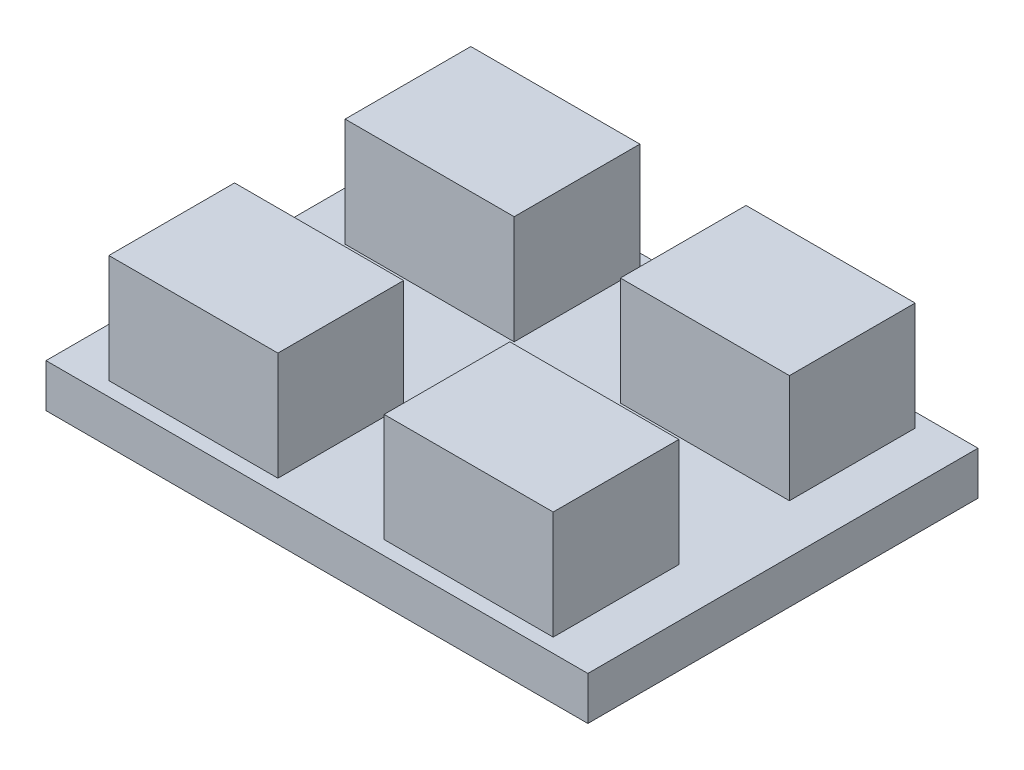
SolidWorks part; units mm, degrees
ref_plane "Спереди" through (0, 0, 0) normal (0, 0, 1) x (1, 0, 0)
ref_plane "Сверху" through (0, 0, 0) normal (0, 1, 0) x (1, 0, 0)
ref_plane "Справа" through (0, 0, 0) normal (1, 0, 0) x (0, 0, -1)
sketch "Эскиз1" plane through (0, 0, 0) normal (0, 1, 0) x (1, 0, 0)
  line L1 (-12.5, -9) -> (12.5, -9)
  line L2 (-12.5, -9) -> (-12.5, 9)
  line L3 (-12.5, 9) -> (12.5, 9)
  line L4 (12.5, -9) -> (12.5, 9)
  line L5 (-12.5, -9) -> (12.5, 9) construction
  line L6 (-12.5, 9) -> (12.5, -9) construction
  point P0 (0, 0)
  dimension "D1" = 25
  dimension "D2" = 18
extrude "Бобышка-Вытянуть1" add sketch "Эскиз1" along normal blind 2
sketch "Эскиз2" plane through (0, 2, 0) normal (0, 1, 0) x (1, 0, 0)
  line L0 (2.45, 8.35) -> (2.45, 2.55)
  line L1 (-10.25, 8.35) -> (-2.45, 8.35)
  line L2 (-10.25, 8.35) -> (-10.25, 2.55)
  line L3 (-10.25, 2.55) -> (-2.45, 2.55)
  line L4 (-2.45, 8.35) -> (-2.45, 2.55)
  line L5 (-10.25, 8.35) -> (-2.45, 2.55) construction
  line L6 (-10.25, 2.55) -> (-2.45, 8.35) construction
  line L7 (2.45, 8.35) -> (10.25, 8.35)
  line L8 (10.25, 8.35) -> (10.25, 2.55)
  line L9 (2.45, 2.55) -> (10.25, 2.55)
  line L10 (2.45, -2.55) -> (2.45, -8.35)
  line L11 (2.45, -2.55) -> (10.25, -2.55)
  line L12 (10.25, -2.55) -> (10.25, -8.35)
  line L13 (2.45, -8.35) -> (10.25, -8.35)
  line L14 (-10.25, -2.55) -> (-10.25, -8.35)
  line L15 (-10.25, -2.55) -> (-2.45, -2.55)
  line L16 (-2.45, -2.55) -> (-2.45, -8.35)
  line L17 (-10.25, -8.35) -> (-2.45, -8.35)
  point P0 (-6.35, 5.45)
  point P5 (-6.4545, 5.4104)
  point P6 (0, 0)
  point P22 (0.475, 1.925)
  dimension "D1" = 7.8
  dimension "D2" = 5.8
  dimension "D5" = 5.1
  dimension "D6" = 4.9
  dimension "D7" = 5.45
  dimension "D8" = 6.35
  dimension "D3" = 2
  dimension "D4" = 2
extrude "Бобышка-Вытянуть2" add sketch "Эскиз2" along normal blind 5
